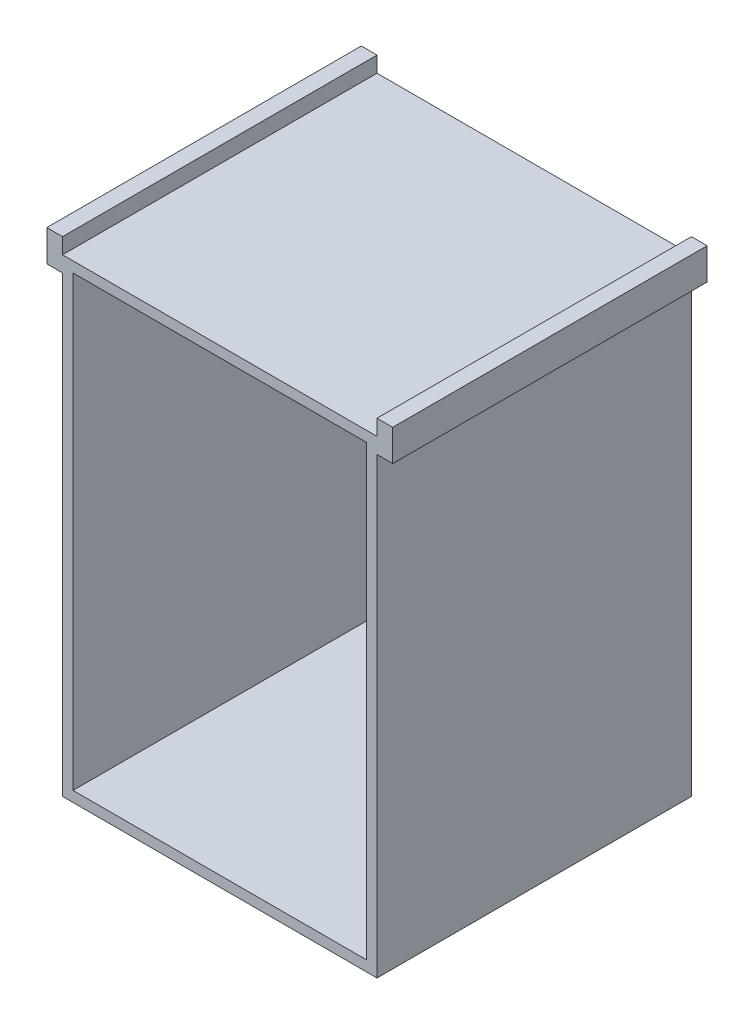
SolidWorks part; units mm, degrees
ref_plane "Front Plane" through (0, 0, 0) normal (0, 0, 1) x (1, 0, 0)
ref_plane "Top Plane" through (0, 0, 0) normal (0, 1, 0) x (1, 0, 0)
ref_plane "Right Plane" through (0, 0, 0) normal (1, 0, 0) x (0, 0, -1)
sketch "Sketch2" plane through (0, 0, 0) normal (0, 1, 0) x (1, 0, 0)
  line L0 (-100.6478, 54.5916) -> (-40.6478, 54.5916)
  line L1 (-40.6478, 54.5916) -> (-40.6478, -5.4084)
  line L2 (-40.6478, -5.4084) -> (-100.6478, -5.4084)
  line L3 (-100.6478, -5.4084) -> (-100.6478, 54.5916)
extrude "Boss-Extrude1" add sketch "Sketch2" along normal blind 89.5
sketch "Sketch3" plane through (0, 0, 5.4084) normal (0, 0, 1) x (1, 0, 0)
  line L3 (-98.6478, 87.5) -> (-42.6478, 87.5)
  line L4 (-42.6478, 87.5) -> (-42.6478, 2)
  line L5 (-42.6478, 2) -> (-98.6478, 2)
  line L6 (-98.6478, 2) -> (-98.6478, 87.5)
extrude "Cut-Extrude1" cut sketch "Sketch3" against normal blind 60
sketch "Sketch4" plane through (0, 89.5, 0) normal (0, 1, 0) x (1, 0, 0)
  line L0 (-100.6478, 54.5916) -> (-103.6478, 54.5916)
  line L1 (-103.6478, 54.5916) -> (-103.6478, -5.4084)
  line L2 (-103.6478, -5.4084) -> (-100.6478, -5.4084)
  line L3 (-100.6478, -5.4084) -> (-100.6478, 54.5916)
  line L4 (-40.6478, 54.5916) -> (-37.6478, 54.5916)
  line L5 (-37.6478, 54.5916) -> (-37.6478, -5.4084)
  line L6 (-37.6478, -5.4084) -> (-40.6478, -5.4084)
  line L7 (-40.6478, -5.4084) -> (-40.6478, 54.5916)
extrude "Boss-Extrude2" add sketch "Sketch4" along normal blind 3 and the other way blind 3
